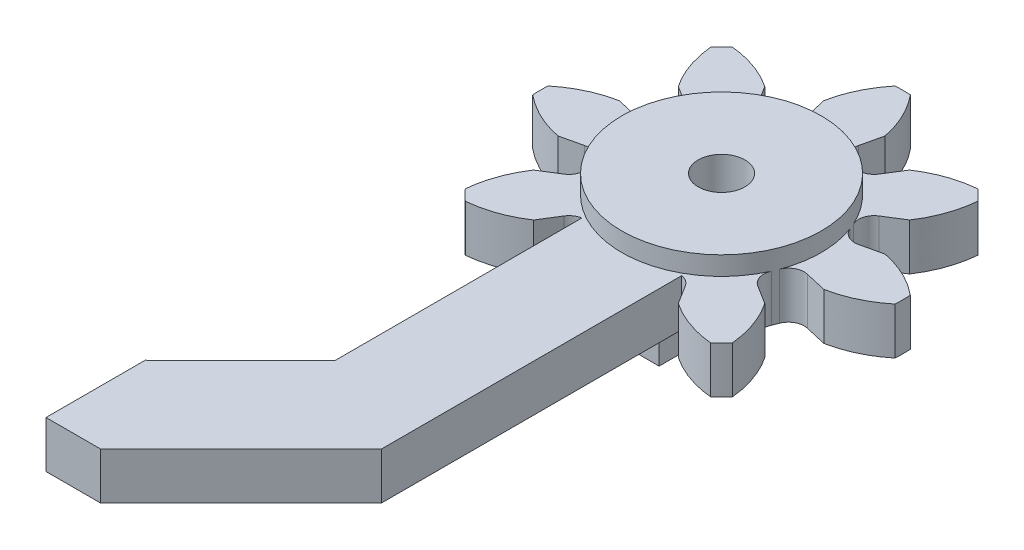
SolidWorks part; units mm, degrees
ref_plane "Front Plane" through (0, 0, 0) normal (0, 0, 1) x (1, 0, 0)
ref_plane "Top Plane" through (0, 0, 0) normal (0, 1, 0) x (1, 0, 0)
ref_plane "Right Plane" through (0, 0, 0) normal (1, 0, 0) x (0, 0, -1)
sketch "Sketch1" plane through (0, 0, 0) normal (0, 1, 0) x (1, 0, 0)
  circle A0 centre (0, 0) radius 6.3937
  dimension "D1" = 12.7875
extrude "Boss-Extrude1" add sketch "Sketch1" along normal blind 4.2
sketch "Sketch2" plane through (0, 0, 0) normal (0, 1, 0) x (1, 0, 0)
  line L0 (0, 0) -> (-1.9595, 8.5166) construction
  line L1 (0, 0) -> (5.1917, 7.0298) construction
  line L2 (0, 0) -> (8.7162, 0.6323) construction
  line L3 (0, 0) -> (6.1519, -6.207) construction
  line L4 (0, 0) -> (-0.71, -8.7103) construction
  line L5 (0, 0) -> (-7.0759, -5.1288) construction
  line L6 (-7.0759, -5.1288) -> (-0.71, -8.7103) construction
  line L7 (-0.71, -8.7103) -> (6.1519, -6.207) construction
  line L8 (6.1519, -6.207) -> (8.7162, 0.6323) construction
  line L9 (8.7162, 0.6323) -> (5.1917, 7.0298) construction
  line L10 (5.1917, 7.0298) -> (-1.9595, 8.5166) construction
  line L11 (5.1917, 7.0298) -> (-0.6838, 11.3691) construction
  line L12 (8.7162, 0.6323) -> (7.6594, 15.2024) construction
  line L13 (6.1519, -6.207) -> (21.7154, 9.2183) construction
  line L14 (-0.71, -8.7103) -> (28.4103, -11.0838) construction
  line L15 (-7.0759, -5.1288) -> (14.3576, -34.6989) construction
  line L16 (0, 0) -> (0, 11.625) construction
  line L17 (0, 0) -> (-1.8143, 9.1213) construction
  line L18 (-1.4336, 6.2309) -> (-1.9595, 8.5166)
  line L19 (1.4336, 6.2309) -> (1.9595, 8.5166)
  line L20 (3.3922, 5.4197) -> (4.6366, 7.4078)
  line L21 (5.4197, 3.3922) -> (7.4078, 4.6366)
  line L22 (6.2309, 1.4336) -> (8.5166, 1.9595)
  line L23 (6.2309, -1.4336) -> (8.5166, -1.9595)
  line L24 (5.4197, -3.3922) -> (7.4078, -4.6366)
  line L25 (3.3922, -5.4197) -> (4.6366, -7.4078)
  line L26 (1.4336, -6.2309) -> (1.9595, -8.5166)
  line L27 (-1.4336, -6.2309) -> (-1.9595, -8.5166)
  line L28 (-3.3922, -5.4197) -> (-4.6366, -7.4078)
  line L29 (-5.4197, -3.3922) -> (-7.4078, -4.6366)
  line L30 (-6.2309, -1.4336) -> (-8.5166, -1.9595)
  line L31 (-6.2309, 1.4336) -> (-8.5166, 1.9595)
  line L32 (-5.4197, 3.3922) -> (-7.4078, 4.6366)
  line L33 (-3.3922, 5.4197) -> (-4.6366, 7.4078)
  circle A0 centre (0, 0) radius 8.7392 construction
  circle A1 centre (0, 0) radius 9.3 construction
  circle A2 centre (0, 0) radius 11.625 construction
  circle A3 centre (0, 0) radius 6.3938 construction
  arc A4 (-0.489, 11.6147) -> (0.489, 11.6147) centre (0, 0) cw
  arc A6 (1.4336, 6.2309) -> (-1.4336, 6.2309) centre (0, 0) ccw
  arc A7 (7.8671, 8.5586) -> (8.5586, 7.8671) centre (0, 0) cw
  arc A8 (5.4197, 3.3922) -> (3.3922, 5.4197) centre (0, 0) ccw
  arc A9 (11.6147, 0.489) -> (11.6147, -0.489) centre (0, 0) cw
  arc A10 (6.2309, -1.4336) -> (6.2309, 1.4336) centre (0, 0) ccw
  arc A11 (8.5586, -7.8671) -> (7.8671, -8.5586) centre (0, 0) cw
  arc A12 (3.3922, -5.4197) -> (5.4197, -3.3922) centre (0, 0) ccw
  arc A13 (0.489, -11.6147) -> (-0.489, -11.6147) centre (0, 0) cw
  arc A14 (-1.4336, -6.2309) -> (1.4336, -6.2309) centre (0, 0) ccw
  arc A15 (-7.8671, -8.5586) -> (-8.5586, -7.8671) centre (0, 0) cw
  arc A16 (-5.4197, -3.3922) -> (-3.3922, -5.4197) centre (0, 0) ccw
  arc A17 (-11.6147, -0.489) -> (-11.6147, 0.489) centre (0, 0) cw
  arc A18 (-6.2309, 1.4336) -> (-6.2309, -1.4336) centre (0, 0) ccw
  arc A19 (-8.5586, 7.8671) -> (-7.8671, 8.5586) centre (0, 0) cw
  arc A20 (-3.3922, 5.4197) -> (-5.4197, 3.3922) centre (0, 0) ccw
  spline S0 degree 3 poles (-1.9595, 8.5166) (-1.1285, 12.8) (8.9048, 17.5947) (34.413, 4.764) (29.5229, -26.838) (14.3576, -34.6989) knots 0 0 0 0 0.160993 0.360844 1 1 1 1 construction
  spline S1 degree 3 poles (-1.9595, 8.5166) (-1.7453, 9.6444) (-1.2236, 10.7314) (-0.489, 11.6147) knots 0 0 0 0 1 1 1 1
  spline S2 degree 3 poles (1.9595, 8.5166) (1.7453, 9.6444) (1.2236, 10.7314) (0.489, 11.6147) knots 0 0 0 0 1 1 1 1
  spline S3 degree 3 poles (4.6366, 7.4078) (5.5855, 8.0537) (6.7231, 8.4535) (7.8671, 8.5586) knots 0 0 0 0 1 1 1 1
  spline S4 degree 3 poles (7.4078, 4.6366) (8.0537, 5.5855) (8.4535, 6.7231) (8.5586, 7.8671) knots 0 0 0 0 1 1 1 1
  spline S5 degree 3 poles (8.5166, 1.9595) (9.6444, 1.7453) (10.7314, 1.2236) (11.6147, 0.489) knots 0 0 0 0 1 1 1 1
  spline S6 degree 3 poles (8.5166, -1.9595) (9.6444, -1.7453) (10.7314, -1.2236) (11.6147, -0.489) knots 0 0 0 0 1 1 1 1
  spline S7 degree 3 poles (7.4078, -4.6366) (8.0537, -5.5855) (8.4535, -6.7231) (8.5586, -7.8671) knots 0 0 0 0 1 1 1 1
  spline S8 degree 3 poles (4.6366, -7.4078) (5.5855, -8.0537) (6.7231, -8.4535) (7.8671, -8.5586) knots 0 0 0 0 1 1 1 1
  spline S9 degree 3 poles (1.9595, -8.5166) (1.7453, -9.6444) (1.2236, -10.7314) (0.489, -11.6147) knots 0 0 0 0 1 1 1 1
  spline S10 degree 3 poles (-1.9595, -8.5166) (-1.7453, -9.6444) (-1.2236, -10.7314) (-0.489, -11.6147) knots 0 0 0 0 1 1 1 1
  spline S11 degree 3 poles (-4.6366, -7.4078) (-5.5855, -8.0537) (-6.7231, -8.4535) (-7.8671, -8.5586) knots 0 0 0 0 1 1 1 1
  spline S12 degree 3 poles (-7.4078, -4.6366) (-8.0537, -5.5855) (-8.4535, -6.7231) (-8.5586, -7.8671) knots 0 0 0 0 1 1 1 1
  spline S13 degree 3 poles (-8.5166, -1.9595) (-9.6444, -1.7453) (-10.7314, -1.2236) (-11.6147, -0.489) knots 0 0 0 0 1 1 1 1
  spline S14 degree 3 poles (-8.5166, 1.9595) (-9.6444, 1.7453) (-10.7314, 1.2236) (-11.6147, 0.489) knots 0 0 0 0 1 1 1 1
  spline S15 degree 3 poles (-7.4078, 4.6366) (-8.0537, 5.5855) (-8.4535, 6.7231) (-8.5586, 7.8671) knots 0 0 0 0 1 1 1 1
  spline S16 degree 3 poles (-4.6366, 7.4078) (-5.5855, 8.0537) (-6.7231, 8.4535) (-7.8671, 8.5586) knots 0 0 0 0 1 1 1 1
  dimension "D1" = 17.4783
  dimension "D2" = 18.6
  dimension "D3" = 23.25
  dimension "D4" = 7.3042
  dimension "D5" = 14.6084
  dimension "D6" = 21.9126
  dimension "D7" = 29.2168
  dimension "D8" = 36.521
  dimension "D9" = 11.25
  dimension "D10" = 8
extrude "Boss-Extrude2" add sketch "Sketch2" along normal blind 3
fillet "Fillet1" radius 1 16 edges at (-1.4336, 1.5, 6.2309) (1.4336, 1.5, 6.2309) (3.3922, 1.5, 5.4197) (-3.3922, 1.5, 5.4197) (-5.4197, 1.5, 3.3922) (-6.2309, 1.5, 1.4336) (6.2309, 1.5, 1.4336) (5.4197, 1.5, -3.3922) (5.4197, 1.5, 3.3922) (6.2309, 1.5, -1.4336) (1.4336, 1.5, -6.2309) (-5.4197, 1.5, -3.3922) (-1.4336, 1.5, -6.2309) (3.3922, 1.5, -5.4197) (-3.3922, 1.5, -5.4197) (-6.2309, 1.5, -1.4336)
sketch "Sketch3" plane through (0, 4.2, 0) normal (0, 1, 0) x (1, 0, 0)
  circle A0 centre (0, 0) radius 1.5
  dimension "D1" = 3
extrude "Cut-Extrude1" cut sketch "Sketch3" against normal through all
sketch "Sketch5" plane through (0, 0, 0) normal (0, -1, 0) x (1, 0, 0)
  line L0 (-3.7506, 0) -> (3.7506, 0) construction
  line L1 (-3.2, 4) -> (3.2, 4)
  line L2 (3.2, 4) -> (3.2, 34)
  line L3 (3.2, 34) -> (-9.3, 34)
  line L4 (-9.3, 34) -> (-9.3, 27.6)
  line L5 (-9.3, 27.6) -> (-3.2, 27.6)
  line L6 (-3.2, 27.6) -> (-3.2, 4)
  point P4 (0, 0)
  point P8 (0, 4)
  dimension "D1" = 6.4
  dimension "D2" = 4
  dimension "D3" = 6.4
  dimension "D4" = 12.5
  dimension "D5" = 30
extrude "Boss-Extrude3" add sketch "Sketch5" against normal blind 3
chamfer "Chamfer1" distance 6 angle 45 1 edges at (-3.2, 1.5, 27.6)
chamfer "Chamfer2" distance 9 angle 45 1 edges at (3.2, 1.5, 34)
sketch "Sketch6" plane through (0, 0, 0) normal (0, -1, 0) x (1, 0, 0)
  line L0 (0, -5) -> (0, 5) construction
  line L2 (-2.5, -6.5) -> (2.5, -6.5)
  line L3 (-2.5, -6.5) -> (-2.5, -3.5)
  line L4 (-2.5, -3.5) -> (2.5, -3.5)
  line L5 (2.5, -6.5) -> (2.5, -3.5)
  line L6 (-2.5, -6.5) -> (2.5, -3.5) construction
  line L7 (-2.5, -3.5) -> (2.5, -6.5) construction
  line L8 (-2.5, 6.5) -> (2.5, 6.5)
  line L9 (-2.5, 6.5) -> (-2.5, 3.5)
  line L10 (-2.5, 3.5) -> (2.5, 3.5)
  line L11 (2.5, 6.5) -> (2.5, 3.5)
  line L12 (-2.5, 6.5) -> (2.5, 3.5) construction
  line L13 (-2.5, 3.5) -> (2.5, 6.5) construction
  point P5 (0, 0)
  dimension "D1" = 10
  dimension "D2" = 3
  dimension "D3" = 3
  dimension "D4" = 5
  dimension "D5" = 5
extrude "Boss-Extrude4" add sketch "Sketch6" along normal blind 2
equation "\"value\"= 7.3042"
equation "\"D4@Sketch2\"=\"value\""
equation "\"D5@Sketch2\"= 2*\"value\""
equation "\"D6@Sketch2\"=3*\"value\""
equation "\"D7@Sketch2\"=4*\"value\""
equation "\"D8@Sketch2\"=5*\"value\""
